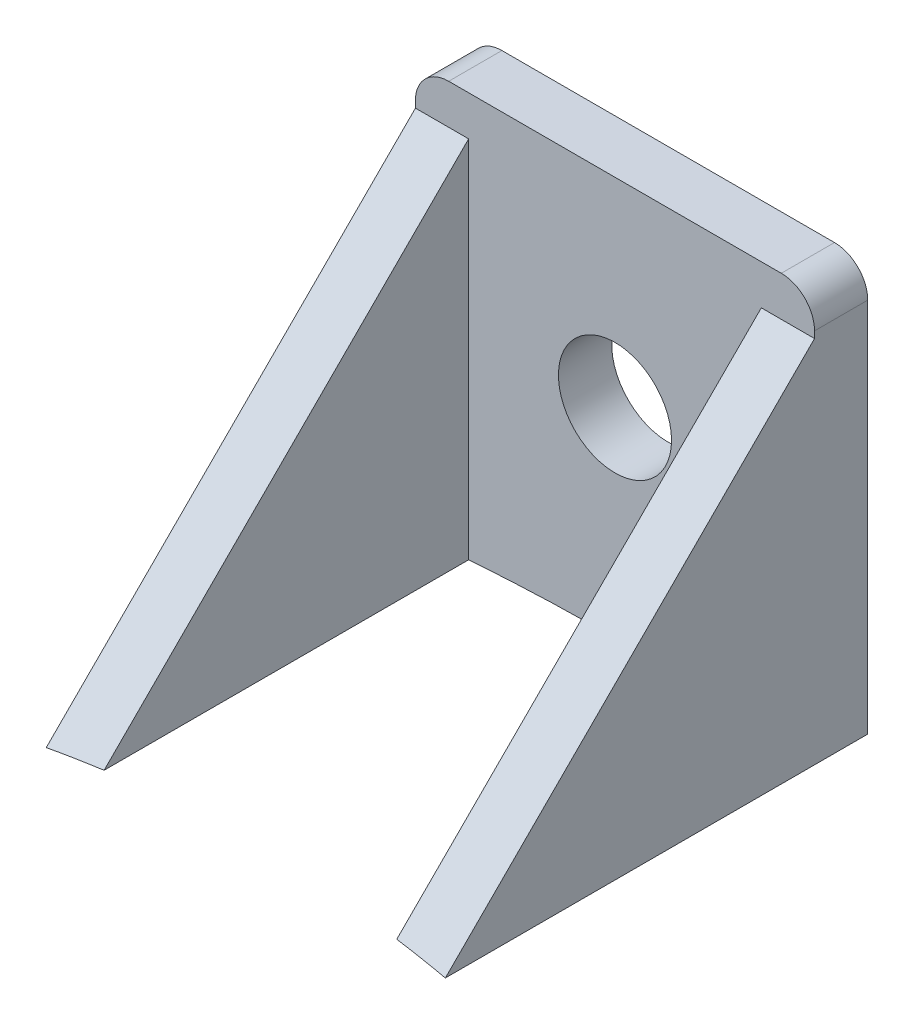
SolidWorks part; units mm, degrees
ref_plane "Face" through (0, 0, 0) normal (0, 0, 1) x (1, 0, 0)
ref_plane "Dessus" through (0, 0, 0) normal (0, 1, 0) x (1, 0, 0)
ref_plane "Droite" through (0, 0, 0) normal (1, 0, 0) x (0, 0, -1)
sketch "Esquisse1" plane through (0, 0, 0) normal (0, 0, 1) x (1, 0, 0)
  line L1 (-15, 15) -> (15, 15)
  line L2 (-15, 15) -> (-15, -18)
  line L3 (-15, -18) -> (15, -18)
  line L4 (15, 15) -> (15, -18)
  circle A0 centre (0, 0) radius 4.25
  dimension "D1" = 15
  dimension "D5" = 8.5
  dimension "D2" = 18
  dimension "D3" = 15
  dimension "D4" = 30
extrude "Boss.-Extru.1" add sketch "Esquisse1" along normal blind 4
fillet "Congé1" radius 2.5 2 edges at (15, 15, 2) (-15, 15, 2)
sketch "Esquisse2" plane through (15, 0, 0) normal (1, 0, 0) x (0, 0, -1)
  line L0 (-4, -18) -> (-34, -18)
  line L1 (-34, -18) -> (-4, 12)
  line L2 (-4, -18) -> (-4, 12)
  dimension "D1" = 45
  dimension "D2" = 30
extrude "Boss.-Extru.2" add sketch "Esquisse2" against normal blind 4
sketch "Esquisse4" plane through (-15, 0, 0) normal (-1, 0, 0) x (0, 0, 1)
  line L0 (4, -18) -> (34, -18)
  line L1 (34, -18) -> (4, 12)
  line L2 (4, 12.5) -> (4, -18) construction
  line L3 (4, 12) -> (34, -18) construction
  line L4 (4, 12) -> (4, -18)
extrude "Boss.-Extru.3" add sketch "Esquisse4" against normal blind 4
sketch "Esquisse5" plane through (0, 0, 0) normal (0, 0, -1) x (-1, 0, 0)
  circle A0 centre (0, -165) radius 150
  circle A1 centre (0, 0) radius 4.25 construction
  dimension "D1" = 300
  dimension "D2" = 165
extrude "Enlèv. mat.-Extru.1" cut sketch "Esquisse5" against normal through all
